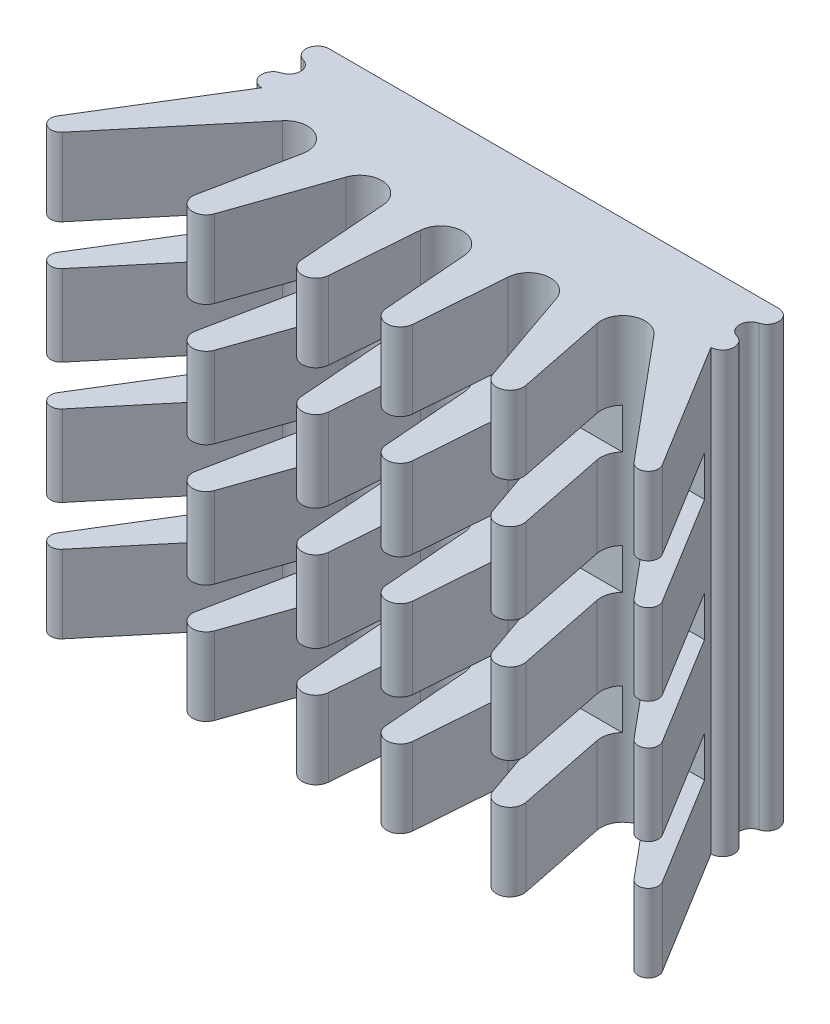
SolidWorks part; units mm, degrees
material "1060 Сплав"
ref_plane "Front" through (0, 0, 0) normal (0, 0, 1) x (1, 0, 0)
ref_plane "Top" through (0, 0, 0) normal (0, 1, 0) x (1, 0, 0)
ref_plane "Right" through (0, 0, 0) normal (1, 0, 0) x (0, 0, -1)
sketch "Эскиз1" plane through (0, 0, 0) normal (0, 1, 0) x (1, 0, 0)
  line L0 (-6.6583, 0) -> (6.6583, 0)
  line L1 (7, -2) -> (7, 0.3046) construction
  line L2 (-7, -2) -> (-7, 0.5048) construction
  line L3 (-6.5, -1.6332) -> (-6.5, -0.359) construction
  line L4 (6.5, -1.5658) -> (6.5, -0.2492) construction
  line L5 (-6.6583, -2) -> (6.6583, -2) construction
  line L6 (0, 0) -> (0, -6.2) construction
  line L7 (-9, -6.2) -> (9, -6.2) construction
  line L8 (-6.6583, -2) -> (-8.9555, -5.7418)
  line L9 (-8.4682, -6.0919) -> (-5.5007, -2.5344)
  line L10 (-4.3609, -3.081) -> (-4.8933, -5.7194)
  line L11 (-4.121, -5.9305) -> (-3.1159, -3.038)
  line L12 (-1.8498, -3.2026) -> (-1.65, -5.8292)
  line L13 (-0.85, -5.8304) -> (-0.65, -3.3006)
  line L14 (0.65, -3.3006) -> (0.85, -5.8304)
  line L15 (1.65, -5.8292) -> (1.8498, -3.2026)
  line L16 (3.1159, -3.038) -> (4.121, -5.9305)
  line L17 (4.8933, -5.7194) -> (4.3609, -3.081)
  line L18 (5.5007, -2.5344) -> (8.4682, -6.0919)
  line L19 (8.9555, -5.7418) -> (6.6583, -2)
  line L20 (-9, -6.2) -> (-9, -4.8881) construction
  line L21 (9, -6.2) -> (9, -4.2175) construction
  line L22 (-1.25, -5.7988) -> (1.25, -5.7988) construction
  line L23 (-0.7995, -2.7) -> (0.9386, -2.7) construction
  line L24 (2.5, -2.6) -> (-2.5, -2.6) construction
  line L25 (5, -2.3) -> (-5, -2.3) construction
  line L26 (4.5, -5.7988) -> (-4.5, -5.7988) construction
  arc A0 (-6.6583, 0) -> (-6.75, -0.6708) centre (-6.6583, -0.3417) ccw
  arc A1 (-6.75, -0.6708) -> (-6.75, -1.3292) centre (-6.8417, -1) cw
  arc A2 (-6.75, -1.3292) -> (-6.6583, -2) centre (-6.6583, -1.6583) ccw
  arc A3 (6.6583, 0) -> (6.75, -0.6708) centre (6.6583, -0.3417) cw
  arc A4 (6.75, -0.6708) -> (6.75, -1.3292) centre (6.8417, -1) ccw
  arc A5 (6.75, -1.3292) -> (6.6583, -2) centre (6.6583, -1.6583) cw
  arc A6 (-5.5007, -2.5344) -> (-4.3609, -3.081) centre (-5, -2.952) cw
  arc A7 (-4.8933, -5.7194) -> (-4.121, -5.9305) centre (-4.5, -5.7988) ccw
  arc A8 (-3.1159, -3.038) -> (-1.8498, -3.2026) centre (-2.5, -3.252) cw
  arc A9 (-1.65, -5.8292) -> (-0.85, -5.8304) centre (-1.25, -5.7988) ccw
  arc A10 (-0.65, -3.3006) -> (0.65, -3.3006) centre (0, -3.352) cw
  arc A11 (-8.4682, -6.0919) -> (-8.9555, -5.7418) centre (-8.6992, -5.8992) cw
  arc A12 (0.85, -5.8304) -> (1.65, -5.8292) centre (1.25, -5.7988) ccw
  arc A13 (1.8498, -3.2026) -> (3.1159, -3.038) centre (2.5, -3.252) cw
  arc A14 (4.121, -5.9305) -> (4.8933, -5.7194) centre (4.5, -5.7988) ccw
  arc A15 (4.3609, -3.081) -> (5.5007, -2.5344) centre (5, -2.952) cw
  arc A16 (8.4682, -6.0919) -> (8.9555, -5.7418) centre (8.6992, -5.8992) ccw
  point P25 (0, -2)
  point P61 (0, -5.7988)
  point P66 (0, -5.7988)
  point P69 (0, 0)
  point P70 (0, 0)
  point P71 (0, -2.6)
  point P72 (0, 0)
  point P73 (0, 0)
  point P74 (0, -2.3)
  point P75 (4.75, -5.8673)
  point P76 (5.0984, -2.4433)
  point P77 (0, 0)
  point P78 (0, 0)
  point P79 (5.774, -2.4741)
  point P80 (5.5977, -2.3825)
  point P81 (0, 0)
  point P82 (4.2411, -2.8749)
  dimension "D7" = 1.3
  dimension "D1" = 13
  dimension "D2" = 14
  dimension "D3" = 2
  dimension "D4" = 6.2
  dimension "D5" = 18
  dimension "D6" = 2.5
  dimension "D8" = 2.7
  dimension "D9" = 2.6
  dimension "D10" = 2.3
  dimension "D11" = 9
  dimension "D12" = 5
  dimension "D13" = 10
  dimension "D14" = 0.8
  dimension "D15" = 0.6
extrude "Бобышка-Вытянуть1" add sketch "Эскиз1" along normal mid plane 13
sketch "Эскиз2" plane through (0, 0, 0) normal (1, 0, 0) x (0, 0, -1)
  line L0 (-6.2, -4.2) -> (-2.5, -4.2)
  line L1 (-2.5, -4.2) -> (-2.5, -3)
  line L2 (-2.5, -3) -> (-6.2, -3)
  line L3 (-6.2, -4.2) -> (-6.2, -3)
  line L4 (-6.2, -0.6) -> (-2.5, -0.6)
  line L5 (-2.5, -0.6) -> (-2.5, 0.6)
  line L6 (-2.5, 0.6) -> (-6.2, 0.6)
  line L7 (-6.2, 0.6) -> (-6.2, -0.6)
  line L8 (-6.2, 3) -> (-2.5, 3)
  line L9 (-2.5, 3) -> (-2.5, 4.2)
  line L10 (-2.5, 4.2) -> (-6.2, 4.2)
  line L11 (-6.2, 4.2) -> (-6.2, 3)
  line L12 (-6.2, 3) -> (-6.2, 0.6) construction
  line L13 (-6.2, -3) -> (-6.2, -0.6) construction
  line L14 (0, 0) -> (-2.5, 0) construction
  line L16 (-6.2, 4.2) -> (-6.2, 6.5) construction
  dimension "D1" = 1.2
  dimension "D2" = 2.4
  dimension "D3" = 2.5
extrude "Вырез-Вытянуть1" cut sketch "Эскиз2" against normal through all both and the other way through all
